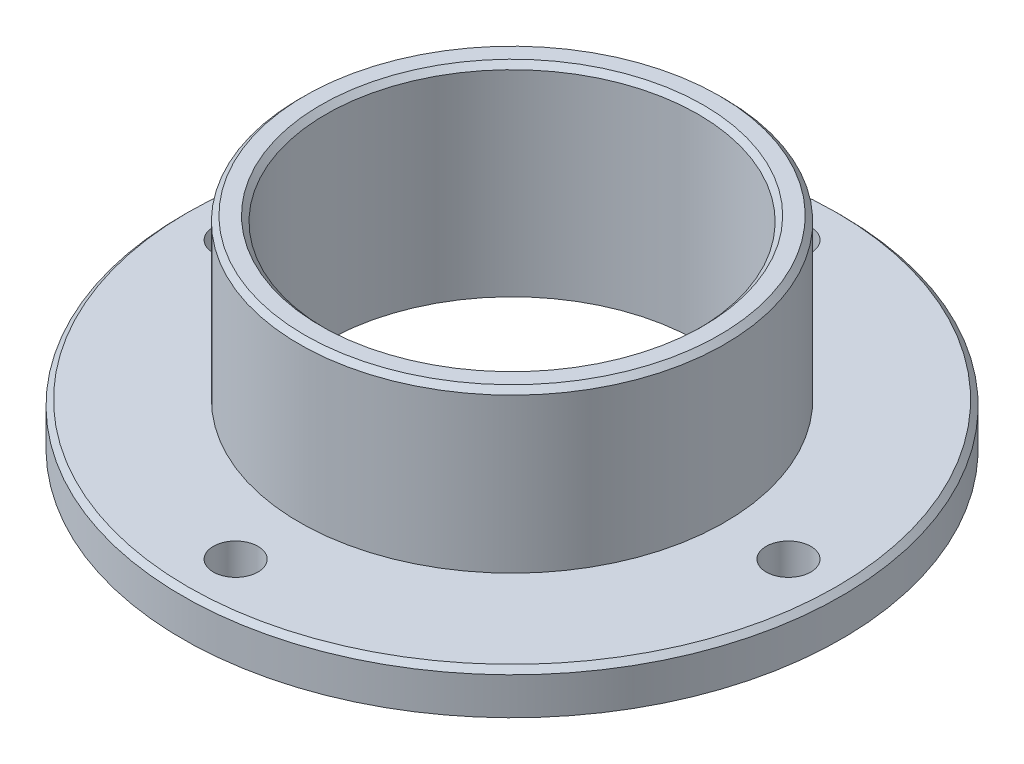
SolidWorks part; units mm, degrees
material "3.3315 (EN-AW 5005)"
ref_plane "Front Plane" through (0, 0, 0) normal (0, 0, 1) x (1, 0, 0)
ref_plane "Top Plane" through (0, 0, 0) normal (0, 1, 0) x (1, 0, 0)
ref_plane "Right Plane" through (0, 0, 0) normal (1, 0, 0) x (0, 0, -1)
sketch "Sketch1" plane through (0, 0, 0) normal (0, 0, 1) x (1, 0, 0)
  line L0 (-31, 0) -> (-17.5, 0)
  line L1 (-17.5, 0) -> (-17.5, 19)
  line L2 (-17.5, 19) -> (-20, 19)
  line L3 (-20, 19) -> (-20, 4)
  line L4 (-20, 4) -> (-31, 4)
  line L5 (-31, 4) -> (-31, 0)
  line L6 (0, 0) -> (0, 31.7764) construction
  line L7 (-28, 0) -> (-28, 4) construction
  line L8 (-23, 4) -> (-23, 0) construction
  dimension "D1" = 35
  dimension "D2" = 15
  dimension "D3" = 5
  dimension "D4" = 4
  dimension "D5" = 3
  dimension "D6" = 3
  dimension "D7" = 40
revolve "Revolve1" add sketch "Sketch1" angle 360 about L6
hole_wizard "Tap Drill for M5 Tap1" positions "Sketch2" profile "Sketch3" hole size "M5" standard "ISO" end condition through all
sketch "Sketch2" plane through (0, 4, 0) normal (0, 1, 0) x (1, 0, 0)
  line L0 (0, 0) -> (0, 26) construction
  point P0 (0, 26)
  dimension "D1" = 26
sketch "Sketch3" plane through (0, 4, -26) normal (1, 0, 0) x (0, 0, 1)
  line L0 (0, 0) -> (0, 4)
  line L1 (0, 4) -> (2.1, 4)
  line L2 (2.1, 4) -> (2.1, 0)
  line L5 (2.1, 0) -> (0, 0)
  line L11 (0, -6.35) -> (0, 107.95) construction
  dimension "Thru Hole Dia." = 4.2
  dimension "Thru Hole Depth" = 4
pattern_circular "CirPattern1" count 4 over 360 about axis through (0, 0, 0) along (0, 1, 0) of "Tap Drill for M5 Tap1"
chamfer "Chamfer1" distance 0.5 angle 45 2 edges at (0, 19, -17.5) (0, 19, -20)
chamfer "Chamfer2" distance 0.5 angle 45 1 edges at (0, 4, -31)
